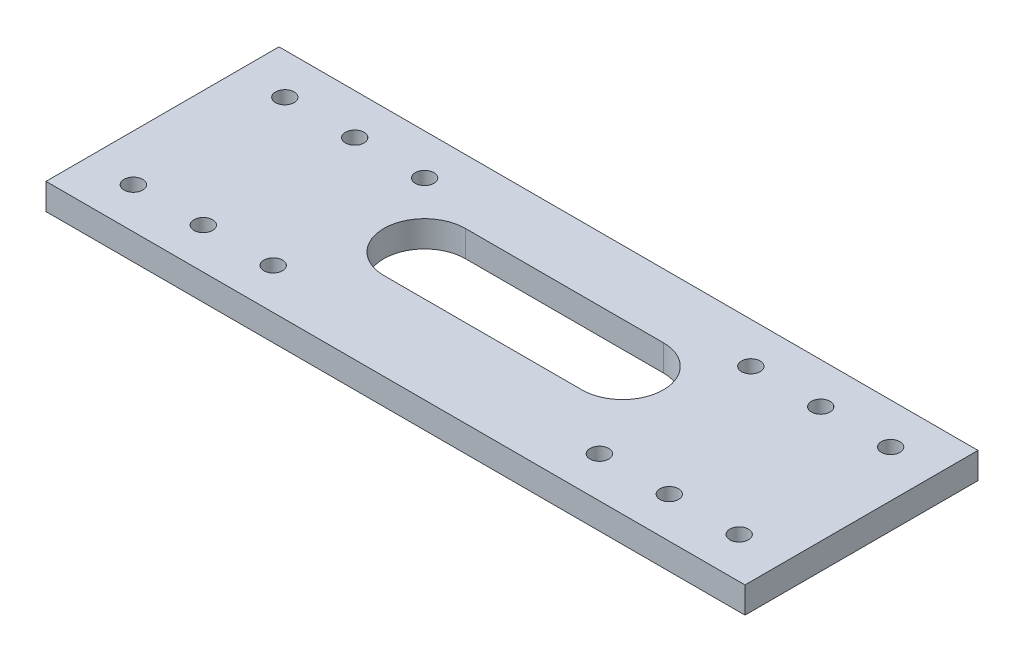
SolidWorks part; units mm, degrees
ref_plane "前视基准面" through (0, 0, 0) normal (0, 0, 1) x (1, 0, 0)
ref_plane "上视基准面" through (0, 0, 0) normal (0, 1, 0) x (1, 0, 0)
ref_plane "右视基准面" through (0, 0, 0) normal (1, 0, 0) x (0, 0, -1)
other "Configuration Table"
sketch "草图1" plane through (0, 0, 0) normal (0, 1, 0) x (1, 0, 0)
  line L1 (0, 0) -> (120, 0)
  line L2 (0, 0) -> (0, 40)
  line L3 (0, 40) -> (120, 40)
  line L4 (120, 0) -> (120, 40)
  dimension "D1" = 40
  dimension "D2" = 120
extrude "凸台-拉伸1" add sketch "草图1" along normal blind 4.5
sketch "草图2" plane through (0, 0, 0) normal (0, -1, 0) x (1, 0, 0)
  line L2 (67, 1) -> (67, 23)
  line L3 (53, 23) -> (53, 1)
  line L4 (67, 1) -> (67, 23) construction
  line L5 (53, 23) -> (53, 1) construction
  line L6 (77, -15) -> (43, -15)
  line L7 (43, -29) -> (77, -29)
  line L8 (77, -15) -> (43, -15)
  line L9 (43, -29) -> (77, -29)
  circle A1 centre (75, 59) radius 2.6
  circle A2 centre (75, 59) radius 2.6 construction
  circle A3 centre (45, 59) radius 2.6
  circle A4 centre (45, 59) radius 2.6 construction
  circle A5 centre (8, -7) radius 1.6
  circle A6 centre (8, -7) radius 1.6
  circle A7 centre (45, 29) radius 2.6
  circle A8 centre (45, 29) radius 2.6 construction
  circle A9 centre (75, 29) radius 2.6
  circle A10 centre (75, 29) radius 2.6 construction
  circle A11 centre (32, -33) radius 1.6
  circle A12 centre (32, -33) radius 1.6
  circle A13 centre (32, -7) radius 1.6
  circle A14 centre (32, -7) radius 1.6
  circle A15 centre (100, -33) radius 1.6
  circle A16 centre (100, -33) radius 1.6
  circle A17 centre (20, -33) radius 1.6
  circle A18 centre (20, -33) radius 1.6
  circle A19 centre (100, -7) radius 1.6
  circle A20 centre (100, -7) radius 1.6
  circle A21 centre (20, -7) radius 1.6
  circle A22 centre (20, -7) radius 1.6
  circle A23 centre (112, -33) radius 1.6
  circle A24 centre (112, -33) radius 1.6
  circle A25 centre (112, -7) radius 1.6
  circle A26 centre (112, -7) radius 1.6
  circle A27 centre (8, -33) radius 1.6
  circle A28 centre (8, -33) radius 1.6
  circle A29 centre (80, 12) radius 7
  circle A30 centre (80, 12) radius 7 construction
  circle A31 centre (40, 12) radius 7
  circle A32 centre (40, 12) radius 7 construction
  circle A33 centre (60, 44) radius 6
  circle A34 centre (60, 44) radius 6 construction
  circle A35 centre (88, -33) radius 1.6
  circle A36 centre (88, -33) radius 1.6
  circle A37 centre (88, -7) radius 1.6
  circle A38 centre (88, -7) radius 1.6
  arc A40 (53, 1) -> (67, 1) centre (60, 1) ccw
  arc A41 (67, 23) -> (53, 23) centre (60, 23) ccw
  arc A42 (53, 1) -> (67, 1) centre (60, 1) ccw construction
  arc A43 (67, 23) -> (53, 23) centre (60, 23) ccw construction
  arc A44 (77, -29) -> (77, -15) centre (77, -22) ccw
  arc A45 (43, -15) -> (43, -29) centre (43, -22) ccw
  arc A46 (77, -29) -> (77, -15) centre (77, -22) ccw
  arc A47 (43, -15) -> (43, -29) centre (43, -22) ccw
  dimension "D1" = 0
  dimension "D2" = 0
  dimension "D3" = 0
  dimension "D4" = 0
  dimension "D5" = 0
  dimension "D6" = 0
  dimension "D7" = 0
  dimension "D8" = 0
  dimension "D9" = 0
  dimension "D10" = 0
  dimension "D11" = 0
  dimension "D12" = 0
  dimension "D13" = 0
  dimension "D14" = 0
  dimension "D15" = 0
  dimension "D16" = 0
  dimension "D17" = 0
  dimension "D18" = 0
  dimension "D19" = 0
  dimension "D20" = 0
  dimension "D21" = 0
extrude "切除-拉伸1" cut sketch "草图2" against normal through all
